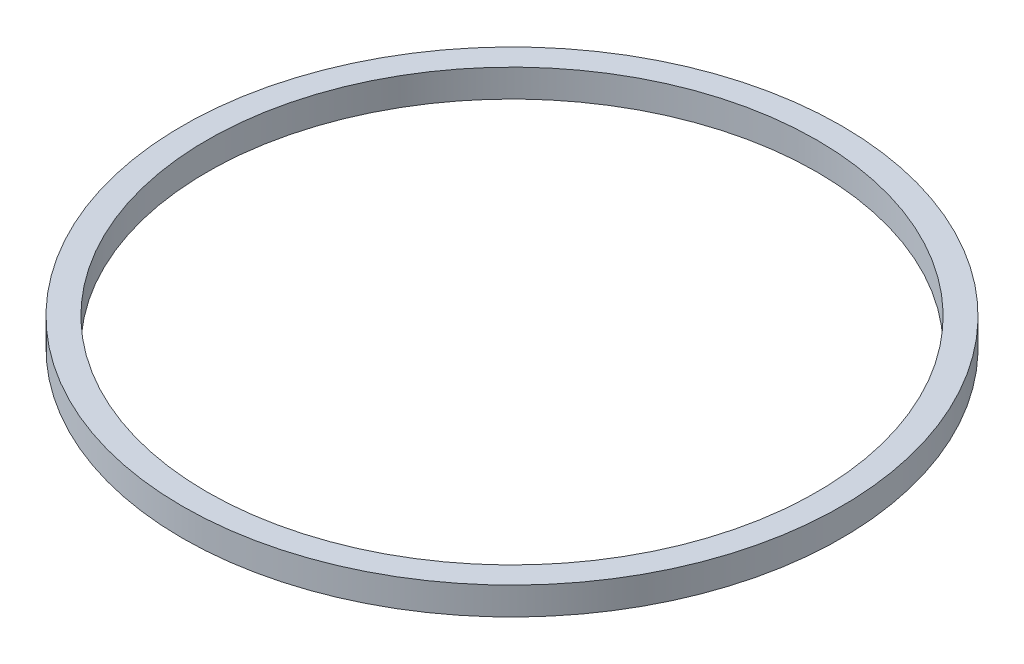
SolidWorks part; units mm, degrees
ref_plane "Front Plane" through (0, 0, 0) normal (0, 0, 1) x (1, 0, 0)
ref_plane "Top Plane" through (0, 0, 0) normal (0, 1, 0) x (1, 0, 0)
ref_plane "Right Plane" through (0, 0, 0) normal (1, 0, 0) x (0, 0, -1)
sketch "Sketch1" plane through (0, 0, 0) normal (0, 1, 0) x (1, 0, 0)
  circle A0 centre (0, 0) radius 227
  circle A1 centre (0, 0) radius 210
  dimension "D1" = 454
  dimension "D2" = 420
extrude "Boss-Extrude1" add sketch "Sketch1" along normal blind 19.05
